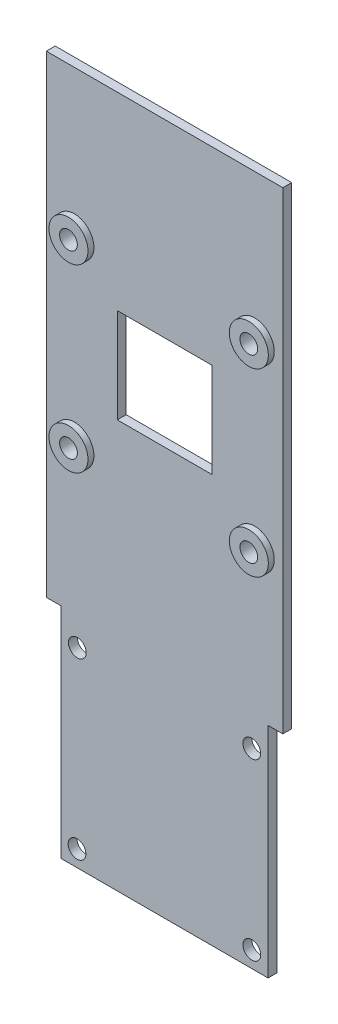
SolidWorks part; units mm, degrees
ref_plane "前视基准面" through (0, 0, 0) normal (0, 0, 1) x (1, 0, 0)
ref_plane "上视基准面" through (0, 0, 0) normal (0, 1, 0) x (1, 0, 0)
ref_plane "右视基准面" through (0, 0, 0) normal (1, 0, 0) x (0, 0, -1)
other "图形1"
sketch "草图2" plane through (0, 0, 0) normal (0, 0, 1) x (1, 0, 0)
  line L0 (-7.1711, 21.18) -> (32.8289, 21.18) construction
  line L1 (-7.1711, 61.18) -> (32.8289, 61.18)
  line L2 (-7.1711, 61.18) -> (-7.1711, -18.82)
  line L3 (-7.1711, -18.82) -> (32.8289, -18.82) construction
  line L4 (32.8289, 61.18) -> (32.8289, -18.82)
  line L5 (12.8289, 61.18) -> (12.8289, -18.82) construction
  line L6 (12.8289, 13.18) -> (20.8289, 13.18)
  line L7 (20.8289, 13.18) -> (20.8289, 29.18)
  line L8 (20.8289, 29.18) -> (4.8289, 29.18)
  line L9 (4.8289, 29.18) -> (4.8289, 13.18)
  line L10 (4.8289, 13.18) -> (12.8289, 13.18)
  line L11 (-7.1711, -18.82) -> (-4.6711, -18.82)
  line L12 (-4.6711, -18.82) -> (-4.6711, -55.82)
  line L13 (-4.6711, -55.82) -> (30.3289, -55.82)
  line L14 (30.3289, -55.82) -> (30.3289, -18.82)
  line L15 (30.3289, -18.82) -> (32.8289, -18.82)
  line L16 (12.8289, -18.82) -> (12.8289, -55.82) construction
  line L17 (-4.7291, -38.32) -> (30.2709, -38.32) construction
  circle A0 centre (-2.4211, 36.43) radius 1.5
  circle A1 centre (28.0789, 36.43) radius 1.5
  circle A2 centre (28.0789, 5.93) radius 1.5
  circle A3 centre (-2.4211, 5.93) radius 1.5
  circle A4 centre (-1.9211, -23.57) radius 1.5
  circle A5 centre (27.5789, -23.57) radius 1.5
  circle A6 centre (-1.9791, -53.07) radius 1.5
  circle A7 centre (27.5789, -53.07) radius 1.5
  point P35 (12.7709, -53.82)
  point P37 (0, 0)
  point P38 (27.5789, -23.57)
  point P39 (27.5789, -53.07)
  dimension "D1" = 15.25
  dimension "D3" = 8
  dimension "D5" = 80
  dimension "D7" = 16
  dimension "D2" = 15.25
  dimension "D4" = 8
  dimension "D6" = 40
  dimension "D8" = 8
  dimension "D9" = 17.5
  dimension "D10" = 17.5
  dimension "D11" = 37
  dimension "D12" = 14.75
  dimension "D13" = 14.75
  dimension "D14" = 14.75
  dimension "D15" = 14.75
  dimension "D16" = 17.5
extrude "凸台-拉伸1" add sketch "草图2" along normal blind 1.5
sketch "草图3" plane through (0, 0, 1.5) normal (0, 0, 1) x (1, 0, 0)
  circle A0 centre (-2.4211, 36.43) radius 1.5
  circle A1 centre (28.0789, 36.43) radius 1.5
  circle A2 centre (28.0789, 5.93) radius 1.5
  circle A3 centre (-2.4211, 5.93) radius 1.5
  circle A4 centre (-2.4211, 36.43) radius 3.3
  circle A5 centre (28.0789, 36.43) radius 3.3
  circle A6 centre (-2.4211, 5.93) radius 3.3
  circle A7 centre (28.0789, 5.93) radius 3.3
extrude "凸台-拉伸2" add sketch "草图3" along normal blind 1
